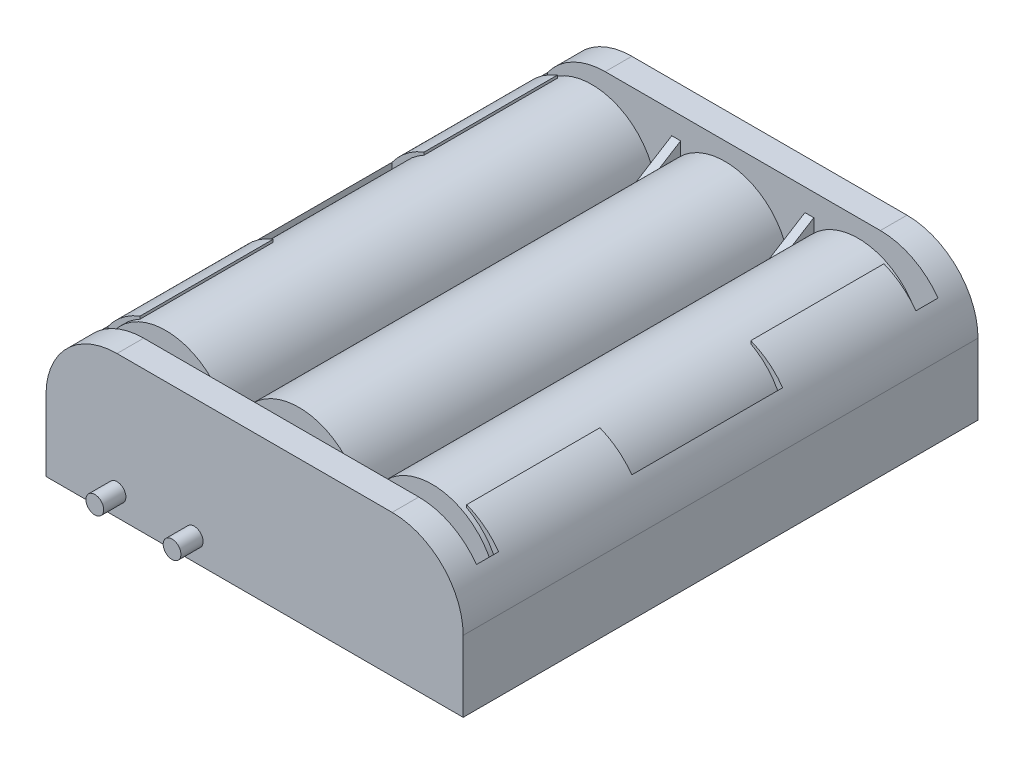
SolidWorks part; units mm, degrees
ref_plane "Front Plane" through (0, 0, 0) normal (0, 0, 1) x (1, 0, 0)
ref_plane "Top Plane" through (0, 0, 0) normal (0, 1, 0) x (1, 0, 0)
ref_plane "Right Plane" through (0, 0, 0) normal (1, 0, 0) x (0, 0, -1)
sketch "Sketch1" plane through (0, 0, 0) normal (0, 1, 0) x (1, 0, 0)
  line L1 (-23.5, -29) -> (23.5, -29)
  line L2 (-23.5, -29) -> (-23.5, 29)
  line L3 (-23.5, 29) -> (23.5, 29)
  line L4 (23.5, -29) -> (23.5, 29)
  line L5 (-23.5, -29) -> (23.5, 29) construction
  line L6 (-23.5, 29) -> (23.5, -29) construction
  point P0 (0, 0)
  dimension "D1" = 47
  dimension "D2" = 58
extrude "Boss-Extrude1" add sketch "Sketch1" along normal blind 16
fillet "Fillet1" radius 8 2 edges at (23.5, 16, 0) (-23.5, 16, 0)
sketch "Sketch2" plane through (0, 16, 0) normal (0, 1, 0) x (1, 0, 0)
  line L0 (0, 0) -> (0, 26) construction
  line L1 (-22, 26) -> (-8, 26)
  line L2 (-22, 26) -> (-22, 23.5)
  line L3 (-22, -26) -> (-8, -26)
  line L4 (-8, 26) -> (-8, -26)
  line L5 (-7, 26) -> (7, 26)
  line L6 (-7, 26) -> (-7, -26)
  line L7 (-7, -26) -> (7, -26)
  line L8 (7, 26) -> (7, -26)
  line L9 (8, 26) -> (22, 26)
  line L10 (8, 26) -> (8, -26)
  line L11 (8, -26) -> (22, -26)
  line L12 (22, 26) -> (22, 23.5)
  line L13 (0, 0) -> (7, 0) construction
  line L14 (22, 8.5) -> (18.4, 8.5)
  line L15 (22, -23.5) -> (18.4, -23.5)
  line L17 (22, -8.5) -> (18.4, -8.5)
  line L18 (18.4, -23.5) -> (18.4, -8.5)
  line L19 (18.4, 23.5) -> (18.4, 8.5)
  line L20 (22, 23.5) -> (18.4, 23.5)
  line L23 (-22, 23.5) -> (-18.4, 23.5)
  line L24 (-18.4, 23.5) -> (-18.4, 8.5)
  line L25 (-22, 8.5) -> (-18.4, 8.5)
  line L26 (-22, -8.5) -> (-18.4, -8.5)
  line L27 (-18.4, -23.5) -> (-18.4, -8.5)
  line L28 (-22, -23.5) -> (-18.4, -23.5)
  line L30 (-22, 8.5) -> (-22, -8.5)
  line L31 (-22, -23.5) -> (-22, -26)
  line L32 (22, 8.5) -> (22, -8.5)
  line L33 (22, -23.5) -> (22, -26)
  dimension "D1" = 14
  dimension "D2" = 52
  dimension "D3" = 1
  dimension "D4" = 3.6
  dimension "D5" = 15
  dimension "D6" = 17
extrude "Cut-Extrude1" cut sketch "Sketch2" against normal blind 14
sketch "Sketch3" plane through (8, 0, 0) normal (1, 0, 0) x (0, 0, -1)
  line L0 (-26, 16) -> (-26, 13.5)
  line L1 (-26, 12.6637) -> (-26, 16) construction
  line L2 (-26, 13.5) -> (-17.5, 8.2)
  line L3 (-17.5, 8.2) -> (17.5, 8.2)
  line L4 (0, 0) -> (0, 8.2) construction
  line L5 (-29, 0) -> (29, 0) construction
  line L6 (26, 16) -> (-26, 16) construction
  line L7 (26, 16) -> (26, 13.5)
  line L8 (26, 13.5) -> (17.5, 8.2)
  line L9 (26, 16) -> (-26, 16)
  dimension "D1" = 2.5
  dimension "D2" = 7.8
  dimension "D3" = 8.5
extrude "Cut-Extrude2" cut sketch "Sketch3" against normal up to surface (16 mm away) up to face at (-8, 9, 0)
sketch "Sketch4" plane through (0, 0, 0) normal (0, 0, 1) x (1, 0, 0)
  line L0 (-8, 2) -> (-22, 2) construction
  line L1 (-8, 2) -> (-22, 2) construction
  line L2 (7, 2) -> (-7, 2) construction
  line L3 (7, 2) -> (-7, 2) construction
  line L4 (22, 2) -> (8, 2) construction
  line L5 (22, 2) -> (8, 2) construction
  line L6 (-15.5, 16) -> (15.5, 16) construction
  circle A0 centre (-15, 8.75) radius 7.25
  circle A1 centre (0, 8.75) radius 7.25
  circle A2 centre (15, 8.75) radius 7.25
  point P9 (-15, 2)
  point P13 (0, 0)
  point P14 (15, 2)
  point P15 (0, 0)
  point P17 (0, 0)
  dimension "D1" = 14.5
extrude "Boss-Extrude3" add sketch "Sketch4" along normal mid plane 48
sketch "Sketch5" plane through (0, 0, 0) normal (0, -1, 0) x (1, 0, 0)
  line L0 (0, 0) -> (0, 29) construction
  line L1 (-23.5, 29) -> (23.5, 29) construction
  line L2 (-23.5, -29) -> (-23.5, 29) construction
  line L3 (-18.8, -26) -> (12.3867, 26)
  line L6 (-12.3867, -26) -> (18.8, 26)
  line L7 (-18.8, -26) -> (18.8, 26) construction
  line L8 (23.5, -29) -> (-23.5, -29) construction
  line L9 (18.8, 26) -> (12.3867, 26)
  line L10 (23.5, 29) -> (23.5, -29) construction
  line L11 (-18.8, -26) -> (-12.3867, -26)
  circle A0 centre (-19.6, 0) radius 1.2
  circle A1 centre (-19.6, 0) radius 2.4
  circle A2 centre (19.6, 0) radius 2.4
  circle A3 centre (19.6, 0) radius 1.2
  point P16 (0, 0)
  point P18 (0, 0)
  dimension "D1" = 2.4
  dimension "D2" = 4.8
  dimension "D3" = 3.9
  dimension "D4" = 5.5
  dimension "D5" = 3
  dimension "D6" = 4.7
  dimension "D7" = 3
extrude "Boss-Extrude4" add sketch "Sketch5" along normal blind 1.5
sketch "Sketch6" plane through (0, 0, 29) normal (0, 0, 1) x (1, 0, 0)
  line L0 (-23.5, 8) -> (-23.5, 0) construction
  line L1 (-23.5, 0) -> (23.5, 0) construction
  circle A0 centre (-15.5, 2.5) radius 1
  circle A1 centre (-6.8, 2.5) radius 1
  point P6 (0, 0)
  point P8 (0, 0)
  point P10 (0, 0)
  dimension "D1" = 2
  dimension "D2" = 8
  dimension "D3" = 8.7
  dimension "D4" = 2.5
extrude "Boss-Extrude5" add sketch "Sketch6" along normal blind 2.5
